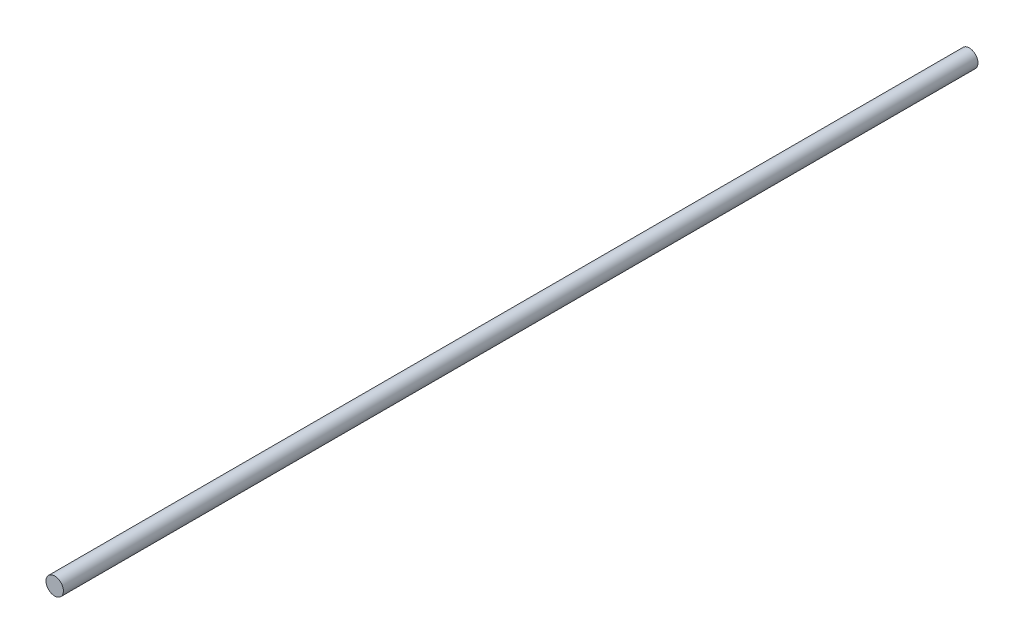
SolidWorks part; units mm, degrees
ref_plane "Front Plane" through (0, 0, 0) normal (0, 0, 1) x (1, 0, 0)
ref_plane "Top Plane" through (0, 0, 0) normal (0, 1, 0) x (1, 0, 0)
ref_plane "Right Plane" through (0, 0, 0) normal (1, 0, 0) x (0, 0, -1)
sketch "Sketch1" plane through (0, 0, 0) normal (0, 0, 1) x (1, 0, 0)
  circle A0 centre (0, 0) radius 20
  dimension "D1" = 40
extrude "Boss-Extrude1" add sketch "Sketch1" along normal blind 2100
sketch "Sketch2" plane through (0, 0, 0) normal (0, 1, 0) x (1, 0, 0)
  line L0 (0, 65) -> (0, 0) construction
  line L1 (-25, 0) -> (25, 0)
  line L2 (-25, 0) -> (-25, 40)
  line L3 (-15, 65) -> (15, 65)
  line L4 (25, 0) -> (25, 40)
  line L5 (15, 65) -> (25, 40)
  line L6 (-25, 40) -> (-15, 65)
  line L7 (20, 0) -> (-20, 0) construction
  point P1 (25, 65)
  point P2 (-25, 65)
  dimension "D1" = 50
  dimension "D2" = 10
  dimension "D3" = 25
  dimension "D4" = 25
  dimension "D5" = 10
  dimension "D6" = 65
sketch "Sketch3" plane through (0, 0, 0) normal (0, 1, 0) x (1, 0, 0)
  circle A0 centre (0, 40) radius 10
  dimension "D1" = 20
  dimension "D2" = 40
